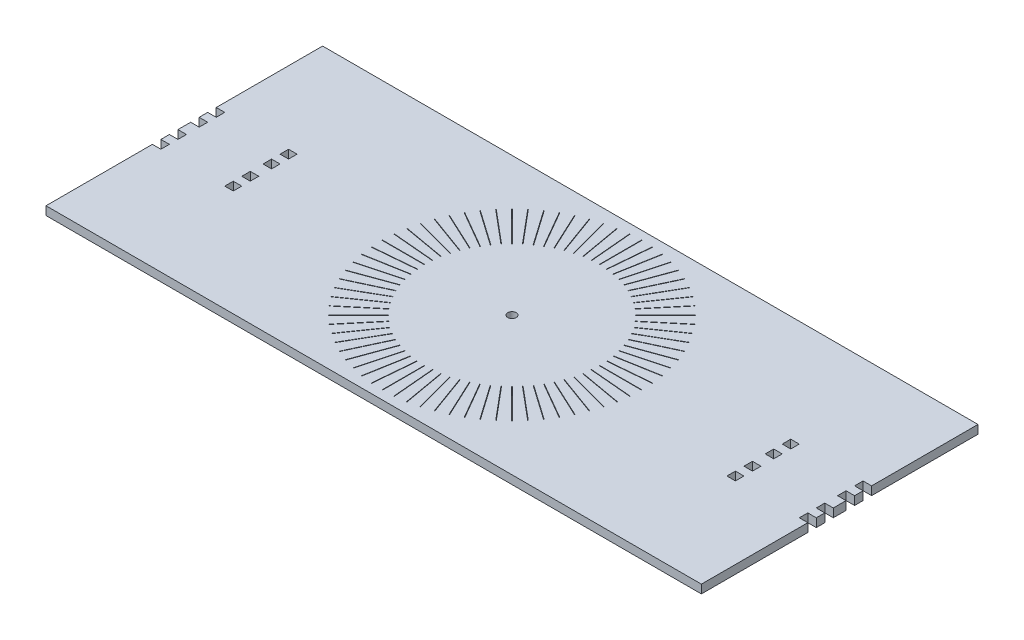
SolidWorks part; units mm, degrees
ref_plane "Front Plane" through (0, 0, 0) normal (0, 0, 1) x (1, 0, 0)
ref_plane "Top Plane" through (0, 0, 0) normal (0, 1, 0) x (1, 0, 0)
ref_plane "Right Plane" through (0, 0, 0) normal (1, 0, 0) x (0, 0, -1)
sketch "Sketch1" plane through (0, 0, 0) normal (0, 1, 0) x (1, 0, 0)
  line L0 (43.1985, 87.9487) -> (43.1985, -77.1513) construction
  line L1 (-152.3815, 87.9487) -> (238.7785, 87.9487)
  line L2 (-152.3815, 87.9487) -> (-152.3815, -77.1513)
  line L3 (-152.3815, -77.1513) -> (238.7785, -77.1513)
  line L4 (238.7785, 87.9487) -> (238.7785, -77.1513)
  line L5 (-152.3815, 5.3987) -> (238.7785, 5.3987) construction
  line L6 (-152.3815, -13.6513) -> (238.7785, -13.6513) construction
  line L7 (-152.3815, 24.4487) -> (238.7785, 24.4487) construction
  circle A0 centre (43.1985, 5.3987) radius 2.54
  dimension "D3" = 5.08
  dimension "D1" = 391.16
  dimension "D2" = 165.1
  dimension "D4" = 19.05
  dimension "D5" = 19.05
extrude "Boss-Extrude1" add sketch "Sketch1" along normal blind 5.08
sketch "Sketch2" plane through (0, 5.08, 0) normal (0, 1, 0) x (1, 0, 0)
  line L0 (43.1985, 87.9487) -> (43.1985, -77.1513) construction
  line L3 (238.7785, 87.9487) -> (-152.3815, 87.9487) construction
  line L6 (-152.3815, -77.1513) -> (238.7785, -77.1513) construction
  line L7 (-152.3815, 5.3987) -> (238.7785, 5.3987) construction
  line L8 (-152.3815, 87.9487) -> (-152.3815, -77.1513) construction
  line L9 (238.7785, -77.1513) -> (238.7785, 87.9487) construction
  line L10 (-152.3815, -13.6513) -> (238.7785, -13.6513) construction
  line L11 (-152.3815, 24.4487) -> (238.7785, 24.4487) construction
  line L12 (-152.3815, 87.9487) -> (-152.3815, -77.1513) construction
  line L13 (-104.1215, 87.9487) -> (-104.1215, -77.1513) construction
  line L14 (195.5985, 14.2887) -> (195.5985, 9.2087)
  line L15 (-152.3815, 24.4487) -> (-147.3015, 24.4487)
  line L16 (-152.3815, 24.4487) -> (-152.3815, 19.3687)
  line L17 (-152.3815, 19.3687) -> (-147.3015, 19.3687)
  line L18 (-147.3015, 24.4487) -> (-147.3015, 19.3687)
  line L19 (-152.3815, 14.2887) -> (-147.3015, 14.2887)
  line L20 (-152.3815, 14.2887) -> (-152.3815, 9.2087)
  line L21 (-152.3815, 9.2087) -> (-147.3015, 9.2087)
  line L22 (-147.3015, 14.2887) -> (-147.3015, 9.2087)
  line L23 (-152.3815, 1.5887) -> (-147.3015, 1.5887)
  line L24 (-152.3815, 1.5887) -> (-152.3815, -3.4913)
  line L25 (-152.3815, -3.4913) -> (-147.3015, -3.4913)
  line L26 (-147.3015, 1.5887) -> (-147.3015, -3.4913)
  line L27 (-152.3815, -13.6513) -> (-147.3015, -13.6513)
  line L28 (-152.3815, -13.6513) -> (-152.3815, -8.5713)
  line L29 (-152.3815, -8.5713) -> (-147.3015, -8.5713)
  line L30 (-147.3015, -13.6513) -> (-147.3015, -8.5713)
  line L31 (-104.1215, -13.6513) -> (-109.2015, -13.6513)
  line L32 (-104.1215, -13.6513) -> (-104.1215, -8.5713)
  line L33 (-104.1215, -8.5713) -> (-109.2015, -8.5713)
  line L34 (-109.2015, -13.6513) -> (-109.2015, -8.5713)
  line L35 (-104.1215, -3.4913) -> (-109.2015, -3.4913)
  line L36 (-104.1215, -3.4913) -> (-104.1215, 1.5887)
  line L37 (-104.1215, 1.5887) -> (-109.2015, 1.5887)
  line L38 (-109.2015, -3.4913) -> (-109.2015, 1.5887)
  line L39 (-104.1215, 24.4487) -> (-109.2015, 24.4487)
  line L40 (-104.1215, 24.4487) -> (-104.1215, 19.3687)
  line L41 (-104.1215, 19.3687) -> (-109.2015, 19.3687)
  line L42 (-109.2015, 24.4487) -> (-109.2015, 19.3687)
  line L43 (-104.1215, 14.2887) -> (-109.2015, 14.2887)
  line L44 (-104.1215, 14.2887) -> (-104.1215, 9.2087)
  line L45 (-104.1215, 9.2087) -> (-109.2015, 9.2087)
  line L46 (-109.2015, 14.2887) -> (-109.2015, 9.2087)
  line L47 (190.5185, 9.2087) -> (195.5985, 9.2087)
  line L48 (190.5185, 14.2887) -> (190.5185, 9.2087)
  line L49 (190.5185, 14.2887) -> (195.5985, 14.2887)
  line L50 (195.5985, 24.4487) -> (195.5985, 19.3687)
  line L51 (190.5185, 19.3687) -> (195.5985, 19.3687)
  line L52 (190.5185, 24.4487) -> (190.5185, 19.3687)
  line L53 (190.5185, 24.4487) -> (195.5985, 24.4487)
  line L54 (195.5985, -3.4913) -> (195.5985, 1.5887)
  line L55 (190.5185, 1.5887) -> (195.5985, 1.5887)
  line L56 (190.5185, -3.4913) -> (190.5185, 1.5887)
  line L57 (190.5185, -3.4913) -> (195.5985, -3.4913)
  line L58 (195.5985, -13.6513) -> (195.5985, -8.5713)
  line L59 (190.5185, -8.5713) -> (195.5985, -8.5713)
  line L60 (190.5185, -13.6513) -> (190.5185, -8.5713)
  line L61 (190.5185, -13.6513) -> (195.5985, -13.6513)
  line L62 (233.6985, -13.6513) -> (233.6985, -8.5713)
  line L63 (238.7785, -8.5713) -> (233.6985, -8.5713)
  line L64 (238.7785, -13.6513) -> (238.7785, -8.5713)
  line L65 (238.7785, -13.6513) -> (233.6985, -13.6513)
  line L66 (233.6985, 1.5887) -> (233.6985, -3.4913)
  line L67 (238.7785, -3.4913) -> (233.6985, -3.4913)
  line L68 (238.7785, 1.5887) -> (238.7785, -3.4913)
  line L69 (238.7785, 1.5887) -> (233.6985, 1.5887)
  line L70 (233.6985, 14.2887) -> (233.6985, 9.2087)
  line L71 (238.7785, 9.2087) -> (233.6985, 9.2087)
  line L72 (238.7785, 14.2887) -> (238.7785, 9.2087)
  line L73 (238.7785, 14.2887) -> (233.6985, 14.2887)
  line L74 (233.6985, 24.4487) -> (233.6985, 19.3687)
  line L75 (238.7785, 19.3687) -> (233.6985, 19.3687)
  line L76 (238.7785, 24.4487) -> (238.7785, 19.3687)
  line L77 (238.7785, 24.4487) -> (233.6985, 24.4487)
  dimension "D3" = 48.26
  dimension "D4" = 5.08
  dimension "D5" = 5.08
  dimension "D6" = 5.08
  dimension "D7" = 5.08
  dimension "D8" = 5.08
  dimension "D9" = 5.08
  dimension "D10" = 5.08
  dimension "D11" = 5.08
  dimension "D12" = 5.08
  dimension "D13" = 5.08
  dimension "D14" = 5.08
  dimension "D15" = 5.08
  dimension "D16" = 5.08
  dimension "D17" = 5.08
  dimension "D18" = 5.08
  dimension "D19" = 5.08
  dimension "D20" = 5.08
  dimension "D21" = 5.08
  dimension "D22" = 5.08
  dimension "D23" = 5.08
  dimension "D1" = 19.05
  dimension "D2" = 19.05
extrude "Cut-Extrude1" cut sketch "Sketch2" against normal blind 5.08
sketch "Sketch3" plane through (0, 5.08, 0) normal (0, 1, 0) x (1, 0, 0)
  line L0 (-152.3815, 5.3987) -> (238.7785, 5.3987) construction
  line L1 (-152.3815, 9.2087) -> (-152.3815, 1.5887) construction
  line L2 (238.7785, 1.5887) -> (238.7785, 9.2087) construction
  line L3 (43.1985, 87.9487) -> (43.1985, -77.1513) construction
  line L4 (238.7785, 87.9487) -> (-152.3815, 87.9487) construction
  line L5 (-152.3815, -77.1513) -> (238.7785, -77.1513) construction
  line L6 (50.0769, 82.5628) -> (47.8632, 57.2594)
  line L7 (43.0715, 82.8687) -> (43.3255, 82.8687)
  line L8 (43.0715, 82.8687) -> (43.0715, 57.4687)
  line L9 (43.0715, 57.4687) -> (43.3255, 57.4687)
  line L10 (43.3255, 82.8687) -> (43.3255, 57.4687)
  line L11 (49.8239, 82.5849) -> (47.6102, 57.2816)
  line L12 (47.6102, 57.2816) -> (47.8632, 57.2594)
  line L13 (49.8239, 82.5849) -> (50.0769, 82.5628)
  line L14 (56.7761, 81.6697) -> (52.3654, 56.6555)
  line L15 (56.5259, 81.7138) -> (52.1153, 56.6996)
  line L16 (52.1153, 56.6996) -> (52.3654, 56.6555)
  line L17 (56.5259, 81.7138) -> (56.7761, 81.6697)
  line L18 (63.3719, 80.1961) -> (56.7979, 55.6615)
  line L19 (63.1265, 80.2618) -> (56.5525, 55.7273)
  line L20 (56.5525, 55.7273) -> (56.7979, 55.6615)
  line L21 (63.1265, 80.2618) -> (63.3719, 80.1961)
  line L22 (69.8141, 78.1532) -> (61.1268, 54.285)
  line L23 (69.5754, 78.2401) -> (60.8881, 54.3719)
  line L24 (60.8881, 54.3719) -> (61.1268, 54.285)
  line L25 (69.5754, 78.2401) -> (69.8141, 78.1532)
  line L26 (76.0538, 75.5566) -> (65.3193, 52.5364)
  line L27 (75.8236, 75.664) -> (65.0891, 52.6438)
  line L28 (65.0891, 52.6438) -> (65.3193, 52.5364)
  line L29 (75.8236, 75.664) -> (76.0538, 75.5566)
  line L30 (82.0435, 72.4261) -> (69.3435, 50.4291)
  line L31 (81.8235, 72.5531) -> (69.1235, 50.5561)
  line L32 (69.1235, 50.5561) -> (69.3435, 50.4291)
  line L33 (81.8235, 72.5531) -> (82.0435, 72.4261)
  line L34 (87.7375, 68.7855) -> (73.1686, 47.9791)
  line L35 (87.5294, 68.9312) -> (72.9606, 48.1247)
  line L36 (72.9606, 48.1247) -> (73.1686, 47.9791)
  line L37 (87.5294, 68.9312) -> (87.7375, 68.7855)
  line L38 (93.0925, 64.6625) -> (76.7657, 45.205)
  line L39 (92.8979, 64.8258) -> (76.5711, 45.3682)
  line L40 (76.5711, 45.3682) -> (76.7657, 45.205)
  line L41 (92.8979, 64.8258) -> (93.0925, 64.6625)
  line L42 (98.0678, 60.0884) -> (80.1073, 42.1279)
  line L43 (97.8882, 60.268) -> (79.9277, 42.3075)
  line L44 (79.9277, 42.3075) -> (80.1073, 42.1279)
  line L45 (97.8882, 60.268) -> (98.0678, 60.0884)
  line L46 (102.6256, 55.0981) -> (83.168, 38.7713)
  line L47 (102.4623, 55.2927) -> (83.0048, 38.9659)
  line L48 (83.0048, 38.9659) -> (83.168, 38.7713)
  line L49 (102.4623, 55.2927) -> (102.6256, 55.0981)
  line L50 (106.731, 49.7296) -> (85.9246, 35.1607)
  line L51 (106.5853, 49.9377) -> (85.7789, 35.3688)
  line L52 (85.7789, 35.3688) -> (85.9246, 35.1607)
  line L53 (106.5853, 49.9377) -> (106.731, 49.7296)
  line L54 (110.353, 44.0237) -> (88.3559, 31.3237)
  line L55 (110.226, 44.2436) -> (88.2289, 31.5436)
  line L56 (88.2289, 31.5436) -> (88.3559, 31.3237)
  line L57 (110.226, 44.2436) -> (110.353, 44.0237)
  line L58 (113.4638, 38.0238) -> (90.4436, 27.2893)
  line L59 (113.3565, 38.254) -> (90.3362, 27.5195)
  line L60 (90.3362, 27.5195) -> (90.4436, 27.2893)
  line L61 (113.3565, 38.254) -> (113.4638, 38.0238)
  line L62 (116.0399, 31.7756) -> (92.1717, 23.0883)
  line L63 (115.953, 32.0143) -> (92.0848, 23.327)
  line L64 (92.0848, 23.327) -> (92.1717, 23.0883)
  line L65 (115.953, 32.0143) -> (116.0399, 31.7756)
  line L66 (118.0616, 25.3267) -> (93.5271, 18.7527)
  line L67 (117.9959, 25.572) -> (93.4614, 18.998)
  line L68 (93.4614, 18.998) -> (93.5271, 18.7527)
  line L69 (117.9959, 25.572) -> (118.0616, 25.3267)
  line L70 (119.5136, 18.7261) -> (94.4995, 14.3154)
  line L71 (119.4695, 18.9762) -> (94.4554, 14.5656)
  line L72 (94.4554, 14.5656) -> (94.4995, 14.3154)
  line L73 (119.4695, 18.9762) -> (119.5136, 18.7261)
  line L74 (120.3847, 12.0241) -> (95.0814, 9.8103)
  line L75 (120.3626, 12.2771) -> (95.0593, 10.0634)
  line L76 (95.0593, 10.0634) -> (95.0814, 9.8103)
  line L77 (120.3626, 12.2771) -> (120.3847, 12.0241)
  line L78 (120.6685, 5.2717) -> (95.2685, 5.2717)
  line L79 (120.6685, 5.5257) -> (95.2685, 5.5257)
  line L80 (95.2685, 5.5257) -> (95.2685, 5.2717)
  line L81 (120.6685, 5.5257) -> (120.6685, 5.2717)
  line L82 (120.3626, -1.4798) -> (95.0593, 0.7339)
  line L83 (120.3847, -1.2268) -> (95.0814, 0.987)
  line L84 (95.0814, 0.987) -> (95.0593, 0.7339)
  line L85 (120.3847, -1.2268) -> (120.3626, -1.4798)
  line L86 (119.4695, -8.1789) -> (94.4554, -3.7683)
  line L87 (119.5136, -7.9288) -> (94.4995, -3.5181)
  line L88 (94.4995, -3.5181) -> (94.4554, -3.7683)
  line L89 (119.5136, -7.9288) -> (119.4695, -8.1789)
  line L90 (117.9959, -14.7747) -> (93.4614, -8.2007)
  line L91 (118.0616, -14.5294) -> (93.5271, -7.9554)
  line L92 (93.5271, -7.9554) -> (93.4614, -8.2007)
  line L93 (118.0616, -14.5294) -> (117.9959, -14.7747)
  line L94 (115.953, -21.217) -> (92.0848, -12.5297)
  line L95 (116.0399, -20.9783) -> (92.1717, -12.291)
  line L96 (92.1717, -12.291) -> (92.0848, -12.5297)
  line L97 (116.0399, -20.9783) -> (115.953, -21.217)
  line L98 (113.3565, -27.4567) -> (90.3362, -16.7222)
  line L99 (113.4638, -27.2265) -> (90.4436, -16.492)
  line L100 (90.4436, -16.492) -> (90.3362, -16.7222)
  line L101 (113.4638, -27.2265) -> (113.3565, -27.4567)
  line L102 (110.226, -33.4463) -> (88.2289, -20.7463)
  line L103 (110.353, -33.2264) -> (88.3559, -20.5264)
  line L104 (88.3559, -20.5264) -> (88.2289, -20.7463)
  line L105 (110.353, -33.2264) -> (110.226, -33.4463)
  line L106 (106.5853, -39.1403) -> (85.7789, -24.5715)
  line L107 (106.731, -38.9323) -> (85.9246, -24.3634)
  line L108 (85.9246, -24.3634) -> (85.7789, -24.5715)
  line L109 (106.731, -38.9323) -> (106.5853, -39.1403)
  line L110 (102.4623, -44.4954) -> (83.0048, -28.1686)
  line L111 (102.6256, -44.3008) -> (83.168, -27.974)
  line L112 (83.168, -27.974) -> (83.0048, -28.1686)
  line L113 (102.6256, -44.3008) -> (102.4623, -44.4954)
  line L114 (97.8882, -49.4707) -> (79.9277, -31.5102)
  line L115 (98.0678, -49.2911) -> (80.1073, -31.3306)
  line L116 (80.1073, -31.3306) -> (79.9277, -31.5102)
  line L117 (98.0678, -49.2911) -> (97.8882, -49.4707)
  line L118 (92.8979, -54.0284) -> (76.5711, -34.5709)
  line L119 (93.0925, -53.8652) -> (76.7657, -34.4076)
  line L120 (76.7657, -34.4076) -> (76.5711, -34.5709)
  line L121 (93.0925, -53.8652) -> (92.8979, -54.0284)
  line L122 (87.5294, -58.1339) -> (72.9606, -37.3274)
  line L123 (87.7375, -57.9882) -> (73.1686, -37.1817)
  line L124 (73.1686, -37.1817) -> (72.9606, -37.3274)
  line L125 (87.7375, -57.9882) -> (87.5294, -58.1339)
  line L126 (81.8235, -61.7558) -> (69.1235, -39.7588)
  line L127 (82.0435, -61.6288) -> (69.3435, -39.6318)
  line L128 (69.3435, -39.6318) -> (69.1235, -39.7588)
  line L129 (82.0435, -61.6288) -> (81.8235, -61.7558)
  line L130 (75.8236, -64.8667) -> (65.0891, -41.8465)
  line L131 (76.0538, -64.7593) -> (65.3193, -41.7391)
  line L132 (65.3193, -41.7391) -> (65.0891, -41.8465)
  line L133 (76.0538, -64.7593) -> (75.8236, -64.8667)
  line L134 (69.5754, -67.4428) -> (60.8881, -43.5746)
  line L135 (69.8141, -67.3559) -> (61.1268, -43.4877)
  line L136 (61.1268, -43.4877) -> (60.8881, -43.5746)
  line L137 (69.8141, -67.3559) -> (69.5754, -67.4428)
  line L138 (63.1265, -69.4645) -> (56.5525, -44.93)
  line L139 (63.3719, -69.3987) -> (56.7979, -44.8642)
  line L140 (56.7979, -44.8642) -> (56.5525, -44.93)
  line L141 (63.3719, -69.3987) -> (63.1265, -69.4645)
  line L142 (56.5259, -70.9165) -> (52.1153, -45.9023)
  line L143 (56.7761, -70.8723) -> (52.3654, -45.8582)
  line L144 (52.3654, -45.8582) -> (52.1153, -45.9023)
  line L145 (56.7761, -70.8723) -> (56.5259, -70.9165)
  line L146 (49.8239, -71.7876) -> (47.6102, -46.4843)
  line L147 (50.0769, -71.7655) -> (47.8632, -46.4621)
  line L148 (47.8632, -46.4621) -> (47.6102, -46.4843)
  line L149 (50.0769, -71.7655) -> (49.8239, -71.7876)
  line L150 (43.0715, -72.0713) -> (43.0715, -46.6713)
  line L151 (43.3255, -72.0713) -> (43.3255, -46.6713)
  line L152 (43.3255, -46.6713) -> (43.0715, -46.6713)
  line L153 (43.3255, -72.0713) -> (43.0715, -72.0713)
  line L154 (36.32, -71.7655) -> (38.5338, -46.4621)
  line L155 (36.573, -71.7876) -> (38.7868, -46.4843)
  line L156 (38.7868, -46.4843) -> (38.5338, -46.4621)
  line L157 (36.573, -71.7876) -> (36.32, -71.7655)
  line L158 (29.6209, -70.8723) -> (34.0315, -45.8582)
  line L159 (29.871, -70.9165) -> (34.2817, -45.9023)
  line L160 (34.2817, -45.9023) -> (34.0315, -45.8582)
  line L161 (29.871, -70.9165) -> (29.6209, -70.8723)
  line L162 (23.0251, -69.3987) -> (29.5991, -44.8642)
  line L163 (23.2704, -69.4645) -> (29.8444, -44.93)
  line L164 (29.8444, -44.93) -> (29.5991, -44.8642)
  line L165 (23.2704, -69.4645) -> (23.0251, -69.3987)
  line L166 (16.5828, -67.3559) -> (25.2701, -43.4877)
  line L167 (16.8215, -67.4428) -> (25.5088, -43.5746)
  line L168 (25.5088, -43.5746) -> (25.2701, -43.4877)
  line L169 (16.8215, -67.4428) -> (16.5828, -67.3559)
  line L170 (10.3431, -64.7593) -> (21.0776, -41.7391)
  line L171 (10.5733, -64.8667) -> (21.3078, -41.8465)
  line L172 (21.3078, -41.8465) -> (21.0776, -41.7391)
  line L173 (10.5733, -64.8667) -> (10.3431, -64.7593)
  line L174 (4.3535, -61.6288) -> (17.0535, -39.6318)
  line L175 (4.5735, -61.7558) -> (17.2735, -39.7588)
  line L176 (17.2735, -39.7588) -> (17.0535, -39.6318)
  line L177 (4.5735, -61.7558) -> (4.3535, -61.6288)
  line L178 (-1.3405, -57.9882) -> (13.2283, -37.1817)
  line L179 (-1.1325, -58.1339) -> (13.4364, -37.3274)
  line L180 (13.4364, -37.3274) -> (13.2283, -37.1817)
  line L181 (-1.1325, -58.1339) -> (-1.3405, -57.9882)
  line L182 (-6.6956, -53.8652) -> (9.6312, -34.4076)
  line L183 (-6.501, -54.0284) -> (9.8258, -34.5709)
  line L184 (9.8258, -34.5709) -> (9.6312, -34.4076)
  line L185 (-6.501, -54.0284) -> (-6.6956, -53.8652)
  line L186 (-11.6709, -49.2911) -> (6.2896, -31.3306)
  line L187 (-11.4913, -49.4707) -> (6.4692, -31.5102)
  line L188 (6.4692, -31.5102) -> (6.2896, -31.3306)
  line L189 (-11.4913, -49.4707) -> (-11.6709, -49.2911)
  line L190 (-16.2286, -44.3008) -> (3.2289, -27.974)
  line L191 (-16.0654, -44.4954) -> (3.3922, -28.1686)
  line L192 (3.3922, -28.1686) -> (3.2289, -27.974)
  line L193 (-16.0654, -44.4954) -> (-16.2286, -44.3008)
  line L194 (-20.3341, -38.9323) -> (0.4724, -24.3634)
  line L195 (-20.1884, -39.1403) -> (0.6181, -24.5715)
  line L196 (0.6181, -24.5715) -> (0.4724, -24.3634)
  line L197 (-20.1884, -39.1403) -> (-20.3341, -38.9323)
  line L198 (-23.956, -33.2264) -> (-1.959, -20.5264)
  line L199 (-23.829, -33.4463) -> (-1.832, -20.7463)
  line L200 (-1.832, -20.7463) -> (-1.959, -20.5264)
  line L201 (-23.829, -33.4463) -> (-23.956, -33.2264)
  line L202 (-27.0669, -27.2265) -> (-4.0466, -16.492)
  line L203 (-26.9595, -27.4567) -> (-3.9393, -16.7222)
  line L204 (-3.9393, -16.7222) -> (-4.0466, -16.492)
  line L205 (-26.9595, -27.4567) -> (-27.0669, -27.2265)
  line L206 (-29.643, -20.9783) -> (-5.7748, -12.291)
  line L207 (-29.5561, -21.217) -> (-5.6879, -12.5297)
  line L208 (-5.6879, -12.5297) -> (-5.7748, -12.291)
  line L209 (-29.5561, -21.217) -> (-29.643, -20.9783)
  line L210 (-31.6647, -14.5294) -> (-7.1302, -7.9554)
  line L211 (-31.5989, -14.7747) -> (-7.0644, -8.2007)
  line L212 (-7.0644, -8.2007) -> (-7.1302, -7.9554)
  line L213 (-31.5989, -14.7747) -> (-31.6647, -14.5294)
  line L214 (-33.1166, -7.9288) -> (-8.1025, -3.5181)
  line L215 (-33.0725, -8.1789) -> (-8.0584, -3.7683)
  line L216 (-8.0584, -3.7683) -> (-8.1025, -3.5181)
  line L217 (-33.0725, -8.1789) -> (-33.1166, -7.9288)
  line L218 (-33.9878, -1.2268) -> (-8.6845, 0.987)
  line L219 (-33.9657, -1.4798) -> (-8.6623, 0.7339)
  line L220 (-8.6623, 0.7339) -> (-8.6845, 0.987)
  line L221 (-33.9657, -1.4798) -> (-33.9878, -1.2268)
  line L222 (-34.2715, 5.5257) -> (-8.8715, 5.5257)
  line L223 (-34.2715, 5.2717) -> (-8.8715, 5.2717)
  line L224 (-8.8715, 5.2717) -> (-8.8715, 5.5257)
  line L225 (-34.2715, 5.2717) -> (-34.2715, 5.5257)
  line L226 (-33.9657, 12.2771) -> (-8.6623, 10.0634)
  line L227 (-33.9878, 12.0241) -> (-8.6845, 9.8103)
  line L228 (-8.6845, 9.8103) -> (-8.6623, 10.0634)
  line L229 (-33.9878, 12.0241) -> (-33.9657, 12.2771)
  line L230 (-33.0725, 18.9762) -> (-8.0584, 14.5656)
  line L231 (-33.1166, 18.7261) -> (-8.1025, 14.3154)
  line L232 (-8.1025, 14.3154) -> (-8.0584, 14.5656)
  line L233 (-33.1166, 18.7261) -> (-33.0725, 18.9762)
  line L234 (-31.5989, 25.572) -> (-7.0644, 18.998)
  line L235 (-31.6647, 25.3267) -> (-7.1302, 18.7527)
  line L236 (-7.1302, 18.7527) -> (-7.0644, 18.998)
  line L237 (-31.6647, 25.3267) -> (-31.5989, 25.572)
  line L238 (-29.5561, 32.0143) -> (-5.6879, 23.327)
  line L239 (-29.643, 31.7756) -> (-5.7748, 23.0883)
  line L240 (-5.7748, 23.0883) -> (-5.6879, 23.327)
  line L241 (-29.643, 31.7756) -> (-29.5561, 32.0143)
  line L242 (-26.9595, 38.254) -> (-3.9393, 27.5195)
  line L243 (-27.0669, 38.0238) -> (-4.0466, 27.2893)
  line L244 (-4.0466, 27.2893) -> (-3.9393, 27.5195)
  line L245 (-27.0669, 38.0238) -> (-26.9595, 38.254)
  line L246 (-23.829, 44.2436) -> (-1.832, 31.5436)
  line L247 (-23.956, 44.0237) -> (-1.959, 31.3237)
  line L248 (-1.959, 31.3237) -> (-1.832, 31.5436)
  line L249 (-23.956, 44.0237) -> (-23.829, 44.2436)
  line L250 (-20.1884, 49.9377) -> (0.6181, 35.3688)
  line L251 (-20.3341, 49.7296) -> (0.4724, 35.1607)
  line L252 (0.4724, 35.1607) -> (0.6181, 35.3688)
  line L253 (-20.3341, 49.7296) -> (-20.1884, 49.9377)
  line L254 (-16.0654, 55.2927) -> (3.3922, 38.9659)
  line L255 (-16.2286, 55.0981) -> (3.2289, 38.7713)
  line L256 (3.2289, 38.7713) -> (3.3922, 38.9659)
  line L257 (-16.2286, 55.0981) -> (-16.0654, 55.2927)
  line L258 (-11.4913, 60.268) -> (6.4692, 42.3075)
  line L259 (-11.6709, 60.0884) -> (6.2896, 42.1279)
  line L260 (6.2896, 42.1279) -> (6.4692, 42.3075)
  line L261 (-11.6709, 60.0884) -> (-11.4913, 60.268)
  line L262 (-6.501, 64.8258) -> (9.8258, 45.3682)
  line L263 (-6.6956, 64.6625) -> (9.6312, 45.205)
  line L264 (9.6312, 45.205) -> (9.8258, 45.3682)
  line L265 (-6.6956, 64.6625) -> (-6.501, 64.8258)
  line L266 (-1.1325, 68.9312) -> (13.4364, 48.1247)
  line L267 (-1.3405, 68.7855) -> (13.2283, 47.9791)
  line L268 (13.2283, 47.9791) -> (13.4364, 48.1247)
  line L269 (-1.3405, 68.7855) -> (-1.1325, 68.9312)
  line L270 (4.5735, 72.5531) -> (17.2735, 50.5561)
  line L271 (4.3535, 72.4261) -> (17.0535, 50.4291)
  line L272 (17.0535, 50.4291) -> (17.2735, 50.5561)
  line L273 (4.3535, 72.4261) -> (4.5735, 72.5531)
  line L274 (10.5733, 75.664) -> (21.3078, 52.6438)
  line L275 (10.3431, 75.5566) -> (21.0776, 52.5364)
  line L276 (21.0776, 52.5364) -> (21.3078, 52.6438)
  line L277 (10.3431, 75.5566) -> (10.5733, 75.664)
  line L278 (16.8215, 78.2401) -> (25.5088, 54.3719)
  line L279 (16.5828, 78.1532) -> (25.2701, 54.285)
  line L280 (25.2701, 54.285) -> (25.5088, 54.3719)
  line L281 (16.5828, 78.1532) -> (16.8215, 78.2401)
  line L282 (23.2704, 80.2618) -> (29.8444, 55.7273)
  line L283 (23.0251, 80.1961) -> (29.5991, 55.6615)
  line L284 (29.5991, 55.6615) -> (29.8444, 55.7273)
  line L285 (23.0251, 80.1961) -> (23.2704, 80.2618)
  line L286 (29.871, 81.7138) -> (34.2817, 56.6996)
  line L287 (29.6209, 81.6697) -> (34.0315, 56.6555)
  line L288 (34.0315, 56.6555) -> (34.2817, 56.6996)
  line L289 (29.6209, 81.6697) -> (29.871, 81.7138)
  line L290 (36.573, 82.5849) -> (38.7868, 57.2816)
  line L291 (36.32, 82.5628) -> (38.5338, 57.2594)
  line L292 (38.5338, 57.2594) -> (38.7868, 57.2816)
  line L293 (36.32, 82.5628) -> (36.573, 82.5849)
  point P16 (43.1985, 5.3987)
  point P17 (-54.5132, 148.1566)
  point P161 (43.1985, 5.3987)
  dimension "D1" = 0.127
  dimension "D2" = 0.254
  dimension "D3" = 25.4
  dimension "D4" = 5.08
  dimension "D5" = 72
extrude "Cut-Extrude2" cut sketch "Sketch3" against normal blind 5.08
sketch "Sketch4" plane through (0, 5.08, 0) normal (0, 1, 0) x (1, 0, 0)
  line L0 (-152.3815, 5.3987) -> (238.7785, 5.3987)
  line L3 (-152.3815, 9.2087) -> (-152.3815, 1.5887) construction
  line L4 (238.7785, 1.5887) -> (238.7785, 9.2087) construction
  line L5 (43.1985, 87.9487) -> (43.1985, -77.1513)
  line L6 (238.7785, 87.9487) -> (-152.3815, 87.9487) construction
  line L7 (-152.3815, -77.1513) -> (238.7785, -77.1513) construction
